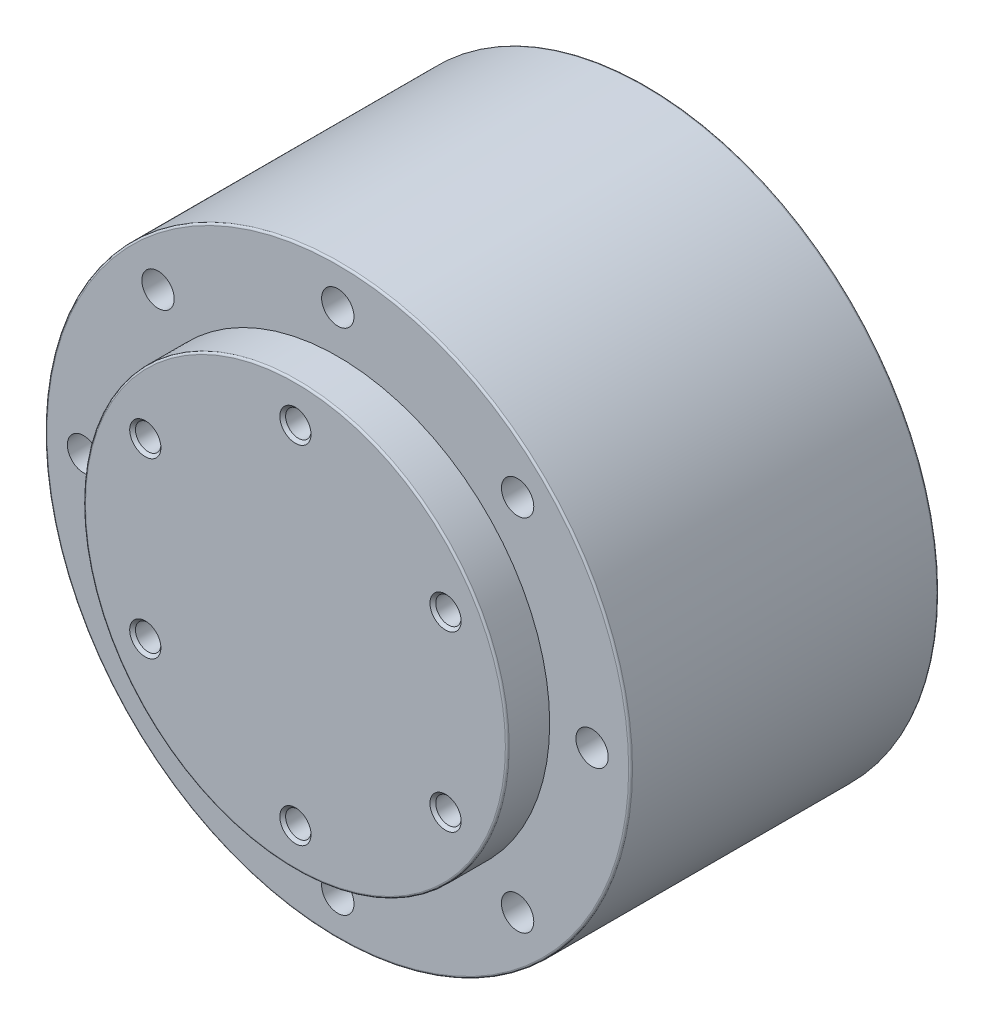
SolidWorks part; units mm, degrees
ref_plane "前视基准面" through (0, 0, 0) normal (0, 0, 1) x (1, 0, 0)
ref_plane "上视基准面" through (0, 0, 0) normal (0, 1, 0) x (1, 0, 0)
ref_plane "右视基准面" through (0, 0, 0) normal (1, 0, 0) x (0, 0, -1)
other "Configuration Table"
sketch "草图1" plane through (0, 0, 0) normal (0, 0, 1) x (1, 0, 0)
  circle A0 centre (0, 0) radius 38
  dimension "D1" = 76
extrude "凸台-拉伸1" add sketch "草图1" along normal mid plane 40
sketch "草图2" plane through (0, 0, 20) normal (0, 0, 1) x (1, 0, 0)
  circle A0 centre (0, 0) radius 27.5
  dimension "D1" = 55
extrude "凸台-拉伸2" add sketch "草图2" along normal blind 5.5
sketch "草图3" plane through (0, 0, -20) normal (0, 0, -1) x (-1, 0, 0)
  circle A0 centre (0, 0) radius 33 construction
  circle A1 centre (0, 33) radius 2.5
  circle A2 centre (23.3345, 23.3345) radius 2.5
  circle A3 centre (33, 0) radius 2.5
  circle A4 centre (23.3345, -23.3345) radius 2.5
  circle A5 centre (0, -33) radius 2.5
  circle A6 centre (-23.3345, -23.3345) radius 2.5
  circle A7 centre (-33, 0) radius 2.5
  circle A8 centre (-23.3345, 23.3345) radius 2.5
  point P21 (0, 0)
  dimension "D1" = 66
  dimension "D2" = 5
  dimension "D3" = 8
hole_wizard "M5 螺纹孔1" positions "3D草图1" profile "草图4" tap size "M5" standard "GB" end condition up to next
sketch3d "3D草图1"
  point P0 (0, 33, -20)
  point P3 (-23.3345, 23.3345, -20)
  point P6 (-33, 0, -20)
  point P9 (-23.3345, -23.3345, -20)
  point P12 (0, -33, -20)
  point P15 (23.3345, -23.3345, -20)
  point P18 (33, 0, -20)
  point P21 (23.3345, 23.3345, -20)
cosmetic thread "孔螺蚊线1" parameters "D2"=5
cosmetic thread "孔螺蚊线2" parameters "D2"=5
cosmetic thread "孔螺蚊线3" parameters "D2"=5
cosmetic thread "孔螺蚊线4" parameters "D2"=5
cosmetic thread "孔螺蚊线5" parameters "D2"=5
cosmetic thread "孔螺蚊线6" parameters "D2"=5
cosmetic thread "孔螺蚊线7" parameters "D2"=5
cosmetic thread "孔螺蚊线8" parameters "D2"=5
sketch "草图4" plane through (0, 33, -20) normal (1, 0, 0) x (0, 1, 0)
  line L0 (0, 0) -> (0, 40)
  line L1 (0, 40) -> (2.1, 40)
  line L2 (2.1, 40) -> (2.1, 0.425)
  line L3 (2.1, 0.425) -> (2.525, 0)
  line L5 (2.525, 0) -> (0, 0)
  line L6 (-2.1, 0.425) -> (-2.525, 0) construction
  line L11 (0, -6.35) -> (0, 107.95) construction
  dimension "通孔螺纹孔钻头直径" = 4.2
  dimension "通孔螺纹孔钻头深度" = 40
  dimension "近端锥形沉头孔直径" = 5.05
  dimension "近端锥形沉头孔角度" = 90
sketch "草图5" plane through (0, 0, 25.5) normal (0, 0, 1) x (1, 0, 0)
  circle A0 centre (0, 0) radius 22.5 construction
  circle A1 centre (0, 22.5) radius 2
  circle A2 centre (19.4856, 11.25) radius 2
  circle A3 centre (19.4856, -11.25) radius 2
  circle A4 centre (0, -22.5) radius 2
  circle A5 centre (-19.4856, -11.25) radius 2
  circle A6 centre (-19.4856, 11.25) radius 2
  point P17 (0, 0)
  dimension "D1" = 45
  dimension "D2" = 4
  dimension "D3" = 6
hole_wizard "M4 螺纹孔1" positions "3D草图2" profile "草图6" tap size "M4" standard "GB"
sketch3d "3D草图2"
  point P0 (0, 22.5, 25.5)
  point P3 (19.4856, 11.25, 25.5)
  point P6 (19.4856, -11.25, 25.5)
  point P9 (0, -22.5, 25.5)
  point P12 (-19.4856, -11.25, 25.5)
  point P15 (-19.4856, 11.25, 25.5)
sketch "草图6" plane through (0, 22.5, 25.5) normal (1, 0, 0) x (0, -1, 0)
  line L0 (0, 0) -> (0, 11.0914)
  line L1 (0, 11.0914) -> (1.65, 10.1)
  line L2 (1.65, 10.1) -> (1.65, 0.375)
  line L3 (1.65, 0.375) -> (2.025, 0)
  line L5 (2.025, 0) -> (0, 0)
  line L6 (-1.65, 0.375) -> (-2.025, 0) construction
  line L10 (0, 11.0914) -> (-1.65, 10.1) construction
  line L11 (0, -6.35) -> (0, 107.95) construction
  dimension "螺纹孔钻头直径" = 3.3
  dimension "螺纹孔钻头深度" = 10.1
  dimension "近端锥形沉头孔直径" = 4.05
  dimension "近端锥形沉头孔角度" = 90
  dimension "导头角度" = 118
cosmetic thread "孔螺蚊线9" parameters "D1"=8, "D2"=4
cosmetic thread "孔螺蚊线10" parameters "D1"=8, "D2"=4
cosmetic thread "孔螺蚊线11" parameters "D1"=8, "D2"=4
cosmetic thread "孔螺蚊线12" parameters "D1"=8, "D2"=4
cosmetic thread "孔螺蚊线13" parameters "D1"=8, "D2"=4
cosmetic thread "孔螺蚊线14" parameters "D1"=8, "D2"=4
fillet "圆角1" radius 0.25 3 edges at (27.5, 0, 25.5) (38, 0, 20) (38, 0, -20)
